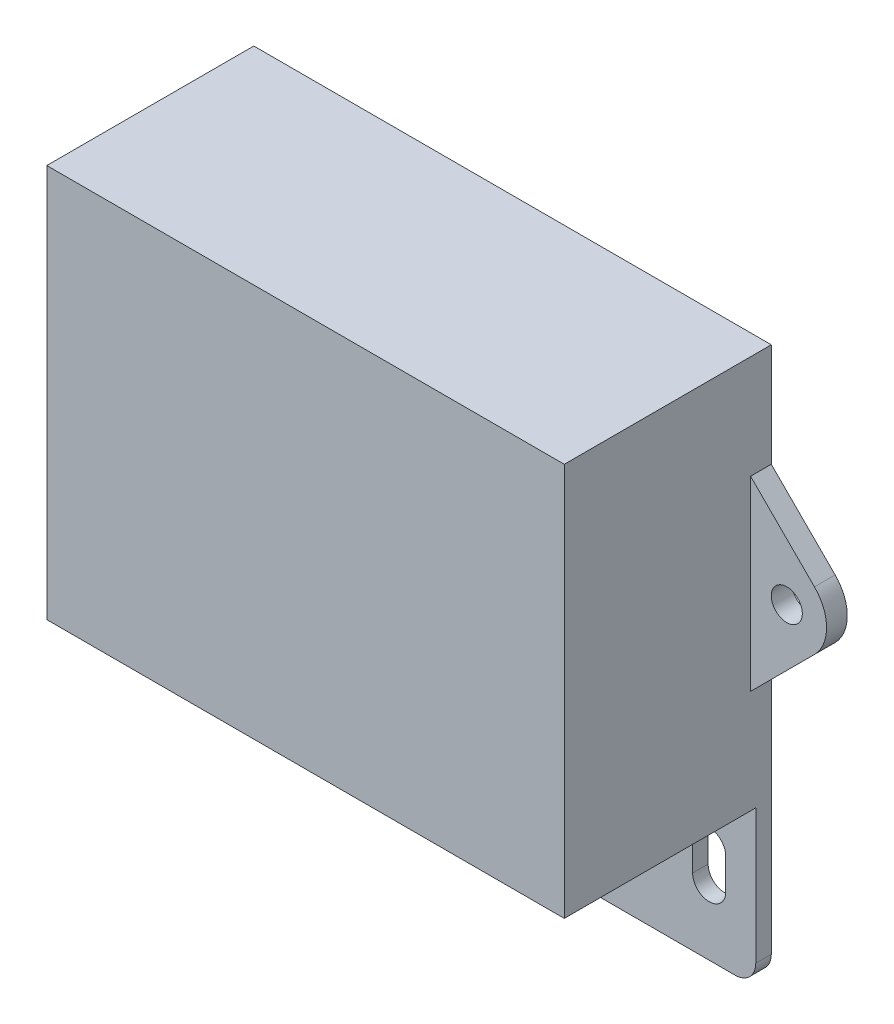
SolidWorks part; units mm, degrees
ref_plane "Plan de face" through (0, 0, 0) normal (0, 0, 1) x (1, 0, 0)
ref_plane "Plan de dessus" through (0, 0, 0) normal (0, 1, 0) x (1, 0, 0)
ref_plane "Plan de droite" through (0, 0, 0) normal (1, 0, 0) x (0, 0, -1)
sketch "Esquisse1" plane through (0, 0, 0) normal (0, 0, 1) x (1, 0, 0)
  line L1 (-25, -19) -> (25, -19)
  line L2 (-25, -19) -> (-25, 19)
  line L3 (-25, 19) -> (25, 19)
  line L4 (25, -19) -> (25, 19)
  line L5 (-25, -19) -> (25, 19) construction
  line L6 (-25, 19) -> (25, -19) construction
  point P0 (0, 0)
  dimension "D1" = 50
  dimension "D2" = 38
extrude "Boss.-Extru.1" add sketch "Esquisse1" along normal blind 20
sketch "Esquisse2" plane through (0, -19, 0) normal (0, -1, 0) x (-1, 0, 0)
  line L0 (25, -20) -> (25, 0) construction
  line L1 (25, -1.5) -> (-25, -1.5)
  line L2 (25, -1.5) -> (25, 0)
  line L3 (25, 0) -> (-25, 0)
  line L4 (-25, -1.5) -> (-25, 0)
  dimension "D1" = 1.5
extrude "Boss.-Extru.2" add sketch "Esquisse2" along normal blind 15
fillet "Congé1" radius 2 2 edges at (25, -34, 0.75) (-25, -34, 0.75)
sketch "Esquisse3" plane through (0, 0, 1.5) normal (0, 0, 1) x (1, 0, 0)
  line L0 (-22.1, -24.5) -> (-22.1, -27.5)
  line L1 (-18.9, -24.5) -> (-18.9, -27.5)
  line L2 (18.9, -24.5) -> (18.9, -27.5)
  line L3 (22.1, -24.5) -> (22.1, -27.5)
  line L4 (-20.5, -24.5) -> (-20.5, -27.5) construction
  line L5 (-22.1, -24.5) -> (-18.9, -24.5) construction
  line L6 (20.5, -24.5) -> (20.5, -27.5) construction
  line L7 (18.9, -27.5) -> (22.1, -27.5) construction
  line L8 (18.9, -24.5) -> (22.1, -24.5) construction
  line L9 (-22.1, -27.5) -> (-18.9, -27.5) construction
  line L10 (23, -34) -> (-23, -34) construction
  line L11 (-25, -32) -> (-25, -19) construction
  line L12 (25, -32) -> (25, -19) construction
  arc A0 (-18.9, -24.5) -> (-22.1, -24.5) centre (-20.5, -24.5) ccw
  arc A1 (-22.1, -27.5) -> (-18.9, -27.5) centre (-20.5, -27.5) ccw
  arc A2 (22.1, -24.5) -> (18.9, -24.5) centre (20.5, -24.5) ccw
  arc A3 (18.9, -27.5) -> (22.1, -27.5) centre (20.5, -27.5) ccw
  point P13 (-20.5, -24.5)
  point P15 (20.5, -24.5)
  point P18 (-22.1, -26)
  point P21 (22.1, -26)
  dimension "D1" = 8
  dimension "D2" = 8
  dimension "D3" = 3.2
  dimension "D4" = 3.2
  dimension "D5" = 3
  dimension "D6" = 4.5
  dimension "D7" = 4.5
  dimension "D8" = 3
extrude "Enlèv. mat.-Extru.1" cut sketch "Esquisse3" against normal through all
sketch "Esquisse4" plane through (0, 0, 0) normal (0, 0, -1) x (-1, 0, 0)
  line L0 (-25, 9) -> (-34, 0)
  line L1 (-25, -32) -> (-25, 19) construction
  line L2 (-34, 0) -> (-25, -9)
  line L3 (25, -9) -> (34, 0)
  line L4 (25, 19) -> (25, -32) construction
  line L5 (34, 0) -> (25, 9)
  line L6 (25, 9) -> (25, -9)
  line L7 (-25, 9) -> (-25, -9)
  line L8 (-34, 0) -> (-25, 0) construction
  line L9 (34, 0) -> (25, 0) construction
  line L10 (-25, 19) -> (25, 19) construction
  line L11 (-28.5, 0) -> (28.5, 0) construction
  circle A2 centre (-28.5, 0) radius 1.5
  circle A3 centre (28.5, 0) radius 1.5
  point P9 (-25, 0)
  point P19 (0, 0)
  dimension "D4" = 3
  dimension "D1" = 10
  dimension "D2" = 28
  dimension "D3" = 19
  dimension "D5" = 57
extrude "Boss.-Extru.3" add sketch "Esquisse4" against normal blind 2
fillet "Congé2" radius 4 2 edges at (-34, 0, 1) (34, 0, 1)
